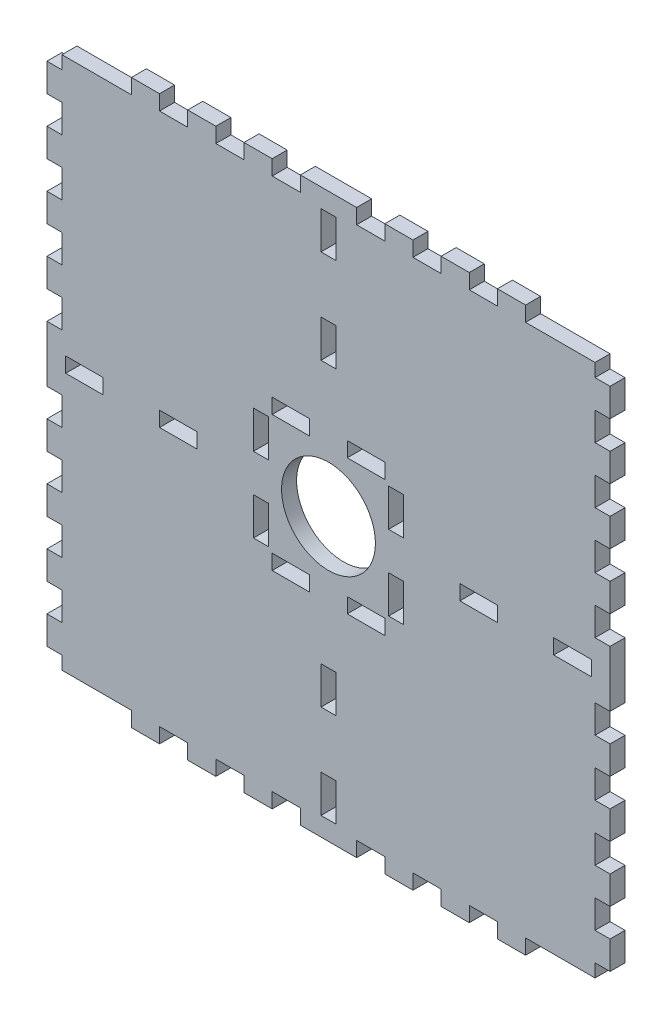
SolidWorks part; units mm, degrees
ref_plane "Plan de face" through (0, 0, 0) normal (0, 0, 1) x (1, 0, 0)
ref_plane "Plan de dessus" through (0, 0, 0) normal (0, 1, 0) x (1, 0, 0)
ref_plane "Plan de droite" through (0, 0, 0) normal (1, 0, 0) x (0, 0, -1)
sketch "Esquisse1" plane through (0, 0, 0) normal (0, 0, 1) x (1, 0, 0)
  line L1 (-150, -150) -> (150, -150)
  line L2 (-150, -150) -> (-150, 150)
  line L3 (-150, 150) -> (150, 150)
  line L4 (150, -150) -> (150, 150)
  line L5 (-150, -150) -> (150, 150) construction
  line L6 (-150, 150) -> (150, -150) construction
  point P0 (0, 0)
  dimension "D1" = 300
  dimension "D2" = 300
extrude "Boss.-Extru.1" add sketch "Esquisse1" along normal blind 8
sketch "Esquisse3" plane through (0, 0, 0) normal (0, 0, 1) x (1, 0, 0)
  line L0 (0, 0) -> (-192.143, 0) construction
  line L2 (-150, -15) -> (-142, -15)
  line L3 (-150, -15) -> (-150, -30)
  line L4 (-150, -30) -> (-142, -30)
  line L5 (-142, -15) -> (-142, -30)
  line L6 (-150, -45) -> (-150, -60)
  line L7 (-150, -45) -> (-142, -45)
  line L8 (-142, -45) -> (-142, -60)
  line L9 (-150, -60) -> (-142, -60)
  line L10 (-150, -75) -> (-150, -90)
  line L11 (-150, -75) -> (-142, -75)
  line L12 (-142, -75) -> (-142, -90)
  line L13 (-150, -90) -> (-142, -90)
  line L14 (-150, -105) -> (-150, -120)
  line L15 (-150, -105) -> (-142, -105)
  line L16 (-142, -105) -> (-142, -120)
  line L17 (-150, -120) -> (-142, -120)
  line L18 (-150, -135) -> (-150, -150)
  line L19 (-150, -135) -> (-142, -135)
  line L20 (-142, -135) -> (-142, -150)
  line L21 (-150, -150) -> (-142, -150)
  line L23 (-150, 60) -> (-142, 60)
  line L24 (-142, 45) -> (-142, 60)
  line L25 (-150, 45) -> (-150, 60)
  line L26 (-150, 135) -> (-142, 135)
  line L27 (-142, 135) -> (-142, 150)
  line L28 (-150, 150) -> (-142, 150)
  line L29 (-150, 135) -> (-150, 150)
  line L30 (-150, 105) -> (-142, 105)
  line L31 (-142, 105) -> (-142, 120)
  line L32 (-150, 120) -> (-142, 120)
  line L33 (-150, 105) -> (-150, 120)
  line L34 (-150, 75) -> (-142, 75)
  line L35 (-142, 75) -> (-142, 90)
  line L36 (-150, 90) -> (-142, 90)
  line L37 (-150, 75) -> (-150, 90)
  line L38 (-150, 45) -> (-142, 45)
  line L39 (-150, 30) -> (-142, 30)
  line L40 (-142, 15) -> (-142, 30)
  line L41 (-150, 15) -> (-142, 15)
  line L42 (-150, 15) -> (-150, 30)
  dimension "D1" = 15
  dimension "D2" = 8
  dimension "D3" = 15
  dimension "D4" = 5
extrude "Enlèv. mat.-Extru.4" cut sketch "Esquisse3" along normal through all
mirror "Symétrie1" about plane through (0, 0, 0) normal (1, 0, 0) of "Enlèv. mat.-Extru.4"
sketch "Esquisse4" plane through (0, 0, 0) normal (0, 0, 1) x (1, 0, 0)
  circle A0 centre (0, 0) radius 25
  dimension "D1" = 50
extrude "Enlèv. mat.-Extru.5" cut sketch "Esquisse4" along normal through all
sketch "Esquisse5" plane through (0, 0, 0) normal (0, 0, 1) x (1, 0, 0)
  line L0 (0, 14.7065) -> (0, 78.1258) construction
  line L1 (15, 142) -> (30, 142)
  line L30 (142, 150) -> (-142, 150) construction
  line L35 (-15, 150) -> (-30, 150)
  line L36 (-15, 150) -> (-15, 142)
  line L37 (-15, 142) -> (-30, 142)
  line L38 (-30, 150) -> (-30, 142)
  line L39 (-45, 150) -> (-45, 142)
  line L40 (-45, 150) -> (-60, 150)
  line L41 (-60, 150) -> (-60, 142)
  line L42 (-45, 142) -> (-60, 142)
  line L43 (-75, 150) -> (-75, 142)
  line L44 (-75, 150) -> (-90, 150)
  line L45 (-90, 150) -> (-90, 142)
  line L46 (-75, 142) -> (-90, 142)
  line L47 (30, 150) -> (30, 142)
  line L48 (-142, 150) -> (-105, 150)
  line L49 (-142, 150) -> (-142, 142)
  line L50 (-142, 142) -> (-105, 142)
  line L51 (-105, 150) -> (-105, 142)
  line L52 (15, 150) -> (30, 150)
  line L53 (15, 150) -> (15, 142)
  line L54 (45, 150) -> (60, 150)
  line L55 (60, 150) -> (60, 142)
  line L56 (45, 142) -> (60, 142)
  line L57 (45, 150) -> (45, 142)
  line L58 (75, 150) -> (90, 150)
  line L59 (90, 150) -> (90, 142)
  line L60 (75, 142) -> (90, 142)
  line L61 (75, 150) -> (75, 142)
  line L62 (142, 142) -> (105, 142)
  line L63 (105, 150) -> (105, 142)
  line L64 (142, 150) -> (105, 150)
  line L65 (142, 150) -> (142, 142)
  dimension "D1" = 15
  dimension "D2" = 15
  dimension "D3" = 8
  dimension "D4" = 15
  dimension "D5" = 3
  dimension "D6" = 8
extrude "Enlèv. mat.-Extru.6" cut sketch "Esquisse5" along normal through all
mirror "Symétrie2" about plane through (0, 0, 0) normal (0, 1, 0) of "Enlèv. mat.-Extru.6"
sketch "Esquisse6" plane through (0, 0, 0) normal (0, 0, 1) x (1, 0, 0)
  line L0 (0, 0) -> (0, -40) construction
  line L1 (-10, -32) -> (-30, -32)
  line L2 (10, -40) -> (30, -40)
  line L3 (10, -40) -> (10, -32)
  line L4 (10, -32) -> (30, -32)
  line L5 (30, -40) -> (30, -32)
  line L6 (-30, -40) -> (-30, -32)
  line L7 (-10, -40) -> (-30, -40)
  line L8 (-10, -40) -> (-10, -32)
  dimension "D1" = 40
  dimension "D2" = 20
  dimension "D3" = 8
  dimension "D4" = 10
extrude "Enlèv. mat.-Extru.7" cut sketch "Esquisse6" along normal through all
mirror "Symétrie3" about plane through (0, 0, 0) normal (0, 1, 0) of "Enlèv. mat.-Extru.7"
pattern_circular "Répétition circulaire1" count 2 every 90 about axis through (0, 0, 0) along (0, 0, 1) of "Enlèv. mat.-Extru.7"
mirror "Symétrie4" about plane through (0, 0, 0) normal (1, 0, 0) of "Répétition circulaire1"
sketch "Esquisse7" plane through (0, 0, 0) normal (0, 0, 1) x (1, 0, 0)
  line L0 (-10, -40) -> (10, -40) construction
  line L1 (0, -40) -> (0, -94.2135) construction
  line L2 (4, -120) -> (4, -140)
  line L3 (4, -70) -> (-4, -70)
  line L4 (4, -70) -> (4, -90)
  line L5 (4, -90) -> (-4, -90)
  line L6 (-4, -70) -> (-4, -90)
  line L7 (4, -70) -> (-4, -90) construction
  line L8 (4, -90) -> (-4, -70) construction
  line L9 (4, -120) -> (-4, -120)
  line L10 (-4, -120) -> (-4, -140)
  line L11 (4, -140) -> (-4, -140)
  point P7 (0, -80)
  dimension "D1" = 30
  dimension "D2" = 20
  dimension "D3" = 8
  dimension "D4" = 2
extrude "Enlèv. mat.-Extru.8" cut sketch "Esquisse7" along normal through all
mirror "Symétrie5" about plane through (0, 0, 0) normal (0, 1, 0) of "Enlèv. mat.-Extru.8"
pattern_circular "Répétition circulaire2" count 2 every 90 about axis through (0, 0, 0) along (0, 0, 1) of "Enlèv. mat.-Extru.8"
mirror "Symétrie6" about plane through (0, 0, 0) normal (1, 0, 0) of "Répétition circulaire2"
